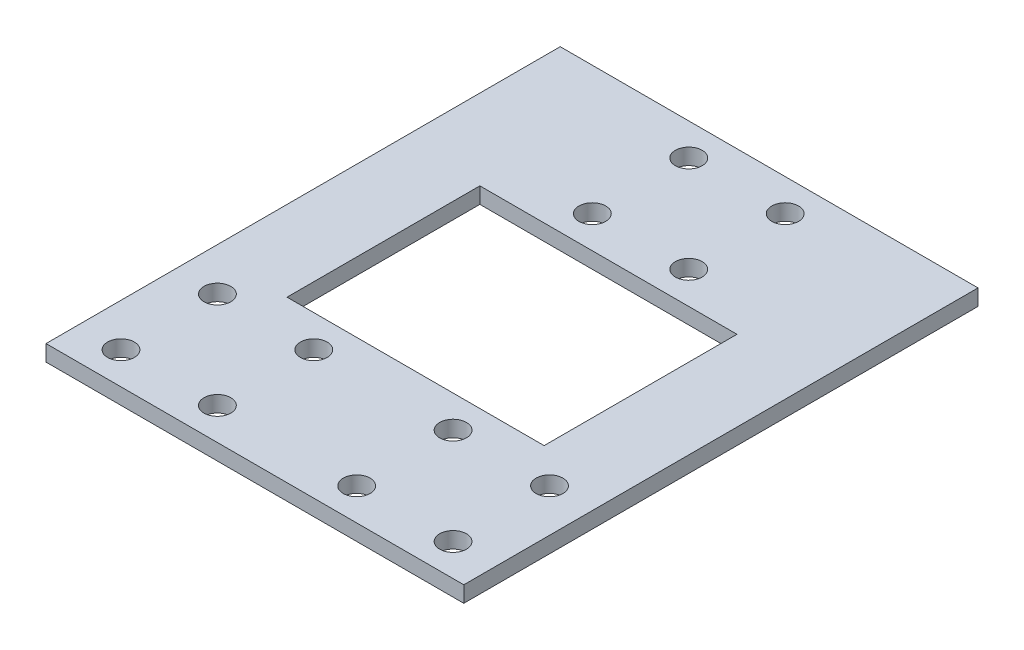
SolidWorks part; units mm, degrees
ref_plane "Front Plane" through (0, 0, 0) normal (0, 0, 1) x (1, 0, 0)
ref_plane "Top Plane" through (0, 0, 0) normal (0, 1, 0) x (1, 0, 0)
ref_plane "Right Plane" through (0, 0, 0) normal (1, 0, 0) x (0, 0, -1)
sketch "Sketch1" plane through (0, 0, 0) normal (0, 1, 0) x (1, 0, 0)
  line L1 (0, 0) -> (78, 0)
  line L2 (0, 0) -> (0, 96)
  line L3 (0, 96) -> (78, 96)
  line L4 (78, 0) -> (78, 96)
  dimension "D1" = 96
  dimension "D2" = 78
extrude "Boss-Extrude1" add sketch "Sketch1" along normal blind 3
sketch "Sketch2" plane through (0, 3, 0) normal (0, 1, 0) x (1, 0, 0)
  line L0 (0, 96) -> (0, 0) construction
  line L2 (0, 0) -> (78, 0) construction
  line L3 (78, 0) -> (78, 96) construction
  line L4 (78, 96) -> (0, 96) construction
  circle A0 centre (8, 6) radius 2.5
  circle A1 centre (26, 6) radius 2.5
  circle A2 centre (8, 24) radius 2.5
  circle A3 centre (26, 24) radius 2.5
  circle A4 centre (52, 6) radius 2.5
  circle A5 centre (70, 6) radius 2.5
  circle A6 centre (70, 24) radius 2.5
  circle A7 centre (52, 24) radius 2.5
  circle A8 centre (48.0013, 72) radius 2.5
  circle A9 centre (30.0013, 72.0005) radius 2.5
  circle A10 centre (48, 90) radius 2.5
  circle A11 centre (30, 90.0005) radius 2.5
  point P32 (30.3108, 96)
  dimension "D1" = 5
  dimension "D4" = 5
  dimension "D6" = 5
  dimension "D7" = 5
  dimension "D8" = 5
  dimension "D10" = 5
  dimension "D11" = 5
  dimension "D13" = 5
  dimension "D14" = 5
  dimension "D15" = 6
  dimension "D16" = 5
  dimension "D19" = 18
  dimension "D2" = 8
  dimension "D3" = 6
  dimension "D5" = 18
  dimension "D9" = 8
  dimension "D12" = 18
  dimension "D17" = 5.9995
  dimension "D18" = 18
  dimension "D20" = 18
  dimension "D21" = 18
  dimension "D23" = 30
  dimension "D24" = 18
  dimension "D25" = 0
extrude "Cut-Extrude1" cut sketch "Sketch2" against normal blind 3
sketch "Sketch3" plane through (0, 3, 0) normal (0, 1, 0) x (1, 0, 0)
  line L0 (78, 0) -> (78, 96) construction
  line L1 (15, 66.0005) -> (63, 66.0005)
  line L2 (15, 66.0005) -> (15, 30)
  line L3 (15, 30) -> (63, 30)
  line L4 (63, 66.0005) -> (63, 30)
  line L5 (0, 96) -> (0, 0) construction
  circle A0 centre (30.0013, 72.0005) radius 2.5 construction
  circle A1 centre (26, 24) radius 2.5 construction
  dimension "D1" = 6
  dimension "D2" = 6
  dimension "D3" = 15
  dimension "D4" = 15
extrude "Cut-Extrude2" cut sketch "Sketch3" against normal blind 3
